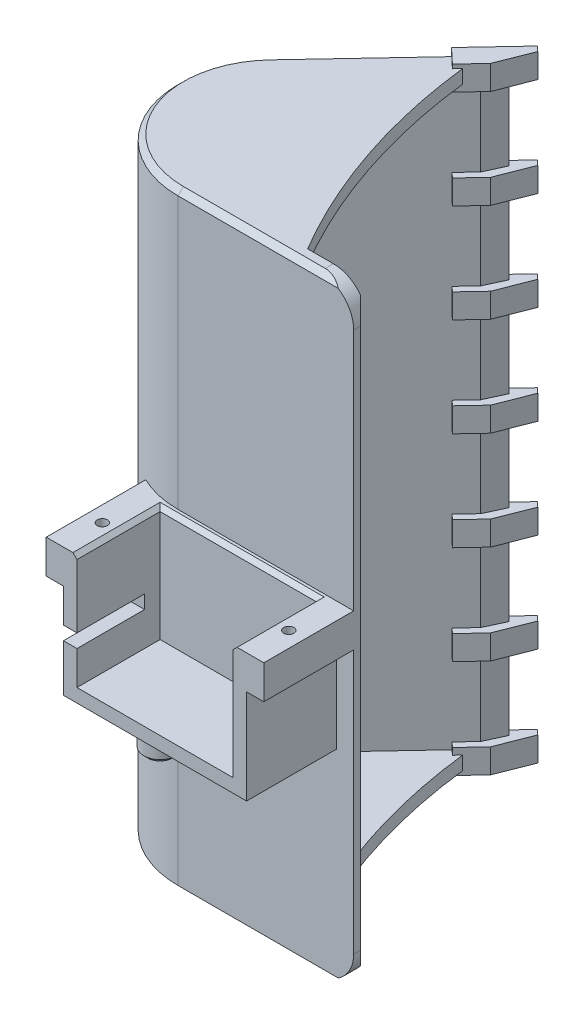
SolidWorks part; units mm, degrees
ref_plane "Front Plane" through (0, 0, 0) normal (0, 0, 1) x (1, 0, 0)
ref_plane "Top Plane" through (0, 0, 0) normal (0, 1, 0) x (1, 0, 0)
ref_plane "Right Plane" through (0, 0, 0) normal (1, 0, 0) x (0, 0, -1)
sketch "Sketch1" plane through (0, 0, 0) normal (0, 1, 0) x (1, 0, 0)
  line L0 (0, 16.7476) -> (0, -16.4893) construction
  line L1 (-14.7696, 0) -> (25.1835, 0) construction
  line L2 (-6.3, 5.3) -> (-6.3, -7)
  line L3 (-6, 5) -> (16.5, 5) construction
  line L4 (-6, 5) -> (-6, -7) construction
  line L5 (-6, -7) -> (0, -7) construction
  line L6 (16.5, 5) -> (16.5, -6) construction
  line L7 (-8.3, -7) -> (-6.3, -7)
  line L8 (16.8, 5.3) -> (16.8, -7)
  line L9 (-6.3, 5.3) -> (16.8, 5.3)
  line L10 (-8.3, 8.3) -> (18.8, 8.3)
  line L11 (18.8, 8.3) -> (18.8, -7)
  line L13 (-8.3, 8.3) -> (-8.3, -7)
  line L15 (16.8, -7) -> (18.8, -7)
  point P17 (18.8, -8.3)
  point P18 (-8.3, -8.3)
  dimension "D2" = 12
  dimension "D3" = 22.5
  dimension "D4" = 6
  dimension "D1" = 0.3
  dimension "D5" = 0.3
  dimension "D6" = 3
  dimension "D7" = 2
  dimension "D8" = 2
  dimension "D9" = 0.3
extrude "Boss-Extrude1" add sketch "Sketch1" against normal blind 17
sketch "Sketch4" plane through (0, 0, 0) normal (0, 1, 0) x (1, 0, 0)
  line L1 (-8.3, 8.3) -> (-10.85, 8.3)
  line L2 (-8.3, 8.3) -> (-8.3, -7)
  line L3 (-8.3, -7) -> (-10.85, -7)
  line L4 (-10.85, 8.3) -> (-10.85, -7)
  line L5 (18.8, -7) -> (18.8, 8.3) construction
  line L6 (18.8, 6.3) -> (21.35, 6.3)
  line L7 (18.8, 6.3) -> (18.8, -7)
  line L8 (18.8, -7) -> (21.35, -7)
  line L9 (21.35, 6.3) -> (21.35, -7)
  line L10 (18.8, 8.3) -> (-8.3, 8.3) construction
extrude "Boss-Extrude4" add sketch "Sketch4" against normal blind 5
chamfer "Chamfer1" distance 0.6 angle 45 3 edges at (16.8, 0, 0.85) (-6.3, 0, 0.85) (5.25, 0, -5.3)
sketch "Sketch2" plane through (0, -17, 0) normal (0, -1, 0) x (1, 0, 0)
  line L0 (-8.3, 7) -> (-6.3, 7) construction
  line L1 (-8.3, 7) -> (18.8, 7)
  line L2 (-8.3, 7) -> (-8.3, -8.3)
  line L3 (-8.3, -8.3) -> (18.8, -8.3)
  line L4 (18.8, 7) -> (18.8, -8.3)
extrude "Boss-Extrude2" add sketch "Sketch2" along normal blind 2
sketch "Sketch3" plane through (0, -19, 0) normal (0, -1, 0) x (1, 0, 0)
  circle A0 centre (0, 1) radius 2.4
  dimension "D1" = 4.8
extrude "Boss-Extrude3" add sketch "Sketch3" along normal blind 6
sketch "Sketch5" plane through (0, 0, 0) normal (0, 1, 0) x (1, 0, 0)
  circle A0 centre (-8.55, -1) radius 0.75
  circle A1 centre (19.05, -1) radius 0.75
  dimension "D1" = 1.5
extrude "Cut-Extrude1" cut sketch "Sketch5" against normal blind 6
sketch "Sketch7" plane through (-8.3, 0, 0) normal (-1, 0, 0) x (0, 0, 1)
  line L0 (0, 17.9571) -> (0, -26.9883) construction
  line L1 (-3, -10) -> (7, -10)
  line L2 (-3, -10) -> (-3, -12)
  line L3 (-3, -12) -> (7, -12)
  line L4 (7, -10) -> (7, -12)
  line L6 (7, -19) -> (7, -5) construction
  line L7 (7, -17) -> (-5.3, -17) construction
  dimension "D1" = 7
  dimension "D2" = 2
  dimension "D4" = 3
extrude "Cut-Extrude2" cut sketch "Sketch7" against normal up to next
ref_plane "Plane1" through (0, -4, 1) normal (0, 1, 0) x (1, 0, 0)
sketch "Sketch8" plane through (0, -4, 1) normal (0, 1, 0) x (1, 0, 0)
  line L0 (-186.9488, 665.0432) -> (361.5632, 1318.7345) construction
  line L2 (21.35, 9.3) -> (-4.65, 9.3)
  line L3 (18.8, 9.3) -> (-10.85, 9.3) construction
  line L5 (21.35, 7.3) -> (-4.65, 7.3)
  line L6 (21.35, 9.3) -> (21.35, 7.3)
  line L7 (2.0906, 49.5215) -> (2.8192, 48.8366)
  line L8 (2.8192, 48.8366) -> (1.4932, 45.9658)
  line L9 (18.8, 9.3) -> (-10.85, 9.3) construction
  line L10 (6.5023, 63.9016) -> (-20.4578, 35.2183) construction
  line L11 (21.35, -6) -> (21.35, 7.3) construction
  line L12 (1.4932, 45.9658) -> (-13.5741, 29.9354)
  line L13 (2.0906, 49.5215) -> (-15.0314, 31.3051)
  line L14 (5.045, 65.2713) -> (-22.1023, 36.389) construction
  line L16 (3.5479, 48.1518) -> (-13.5741, 29.9354) construction
  arc A1 (-4.65, 7.3) -> (-15.0314, 31.3051) centre (-4.65, 21.5474) cw
  arc A3 (-20.4578, 35.2183) -> (-4.65, 9.3) centre (-4.65, 27.0798) ccw construction
  arc A4 (-22.1023, 36.389) -> (-4.65, 7.3) centre (-4.65, 27.0798) ccw construction
  arc A5 (-4.65, 9.3) -> (-13.5741, 29.9354) centre (-4.65, 21.5474) cw
  dimension "D5" = 25
  dimension "D2" = 3
  dimension "D3" = 1
  dimension "D4" = 26
  dimension "D1" = 2
extrude "Boss-Extrude5" add sketch "Sketch8" along normal blind 45 and the other way blind 45
sketch "Sketch11" plane through (0, 41, 0) normal (0, 1, 0) x (1, 0, 0)
  line L0 (-186.9488, 665.0432) -> (361.5632, 1318.7345) construction
  line L4 (0.5371, 46.8687) -> (-15.0314, 30.3051)
  line L5 (13.7534, 6.3) -> (-4.65, 6.3)
  line L10 (-4.65, 6.3) -> (21.35, 6.3) construction
  line L12 (2.0906, 48.5215) -> (-15.0314, 30.3051) construction
  arc A1 (0.5371, 46.8687) -> (13.7534, 6.3) centre (87.8824, 52.8866) ccw
  arc A2 (-15.0314, 30.3051) -> (-4.65, 6.3) centre (-4.65, 20.5474) ccw
  arc A4 (-15.0314, 30.3051) -> (-4.65, 6.3) centre (-4.65, 20.5474) ccw construction
  point P2 (3.4731, 64.0063)
  point P3 (-18.9581, 36.5376)
  point P4 (18.8, 8.3)
  point P5 (-4.5791, 8.3)
  point P13 (1.924, 65.2713)
  point P17 (18.8, 6.3)
extrude "Boss-Extrude6" add sketch "Sketch11" against normal blind 2
mirror "Mirror1" about plane through (0, -4, 1) normal (0, 1, 0) of "Boss-Extrude6"
chamfer "Chamfer2" distance 0.6 angle 45 1 edges at (0, -25, -1.4)
chamfer "Chamfer4" distance 1 angle 45 1 edges at (21.35, -4, -8.3)
chamfer "Chamfer5" distance 0.8 angle 45 6 edges at (8.35, 41, -6.3) (8.35, -49, -6.3) (-17.7269, 41, -14.8921) (-17.7269, -49, -14.8921) (-6.4704, -49, -39.4133) (-6.4704, 41, -39.4133)
sketch "Sketch12" plane through (0, 41, 0) normal (0, 1, 0) x (1, 0, 0)
  line L0 (-2.0187, 44.1496) -> (4.1452, 50.7075)
  line L1 (2.0906, 48.5215) -> (-15.0314, 30.3051) construction
  line L2 (4.1452, 50.7075) -> (4.8739, 50.0226)
  line L3 (4.8739, 50.0226) -> (2.9068, 45.0096)
  line L4 (2.9068, 45.0096) -> (0.1673, 42.0949)
  line L5 (0.1673, 42.0949) -> (-2.0187, 44.1496)
  line L6 (2.8192, 47.8366) -> (2.6735, 47.9736) construction
  line L7 (0.7631, 44.189) -> (1.4932, 44.9658) construction
  dimension "D1" = 1
  dimension "D2" = 3
  dimension "D3" = 4
  dimension "D4" = 1
  dimension "D5" = 5
extrude "Boss-Extrude7" add sketch "Sketch12" against normal blind 3 and the other way blind 0.6
pattern_linear "LPattern1" count 7 spacing 14.6 along (0, -1, 0) of "Boss-Extrude7"
fillet "Fillet1" radius 5 2 edges at (21.35, 41, -7.2) (21.35, -49, -7.2)
